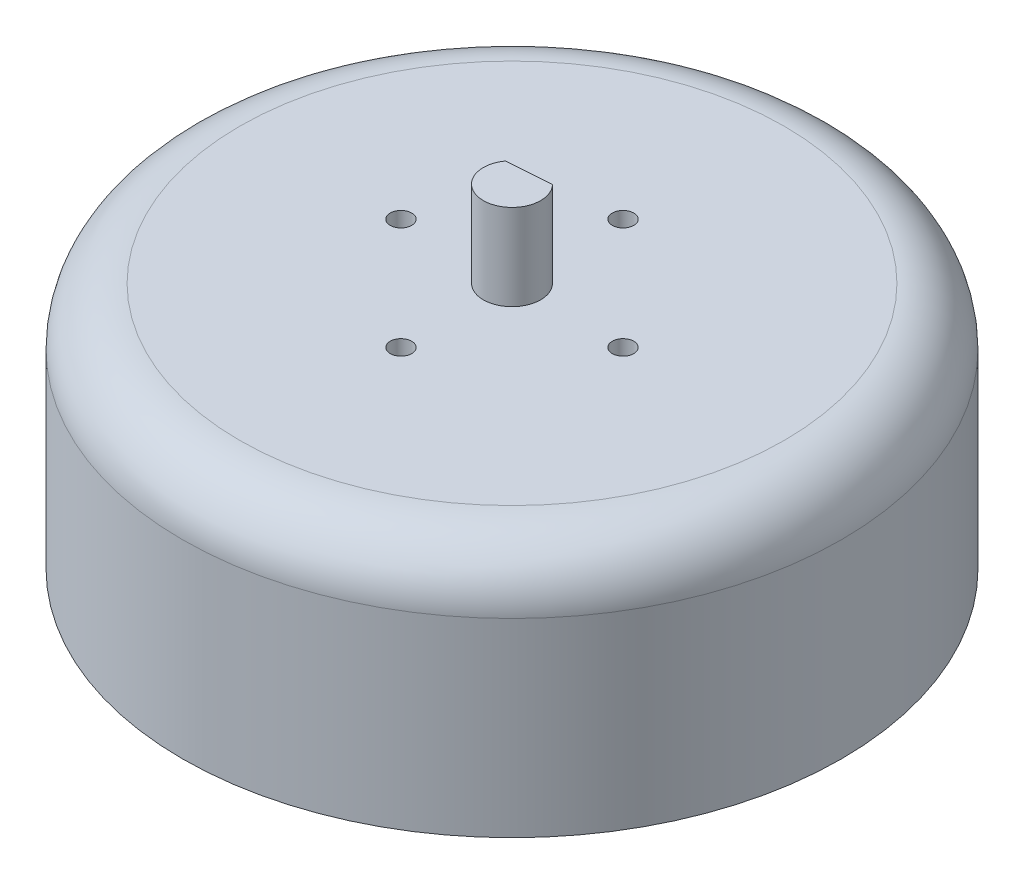
SolidWorks part; units mm, degrees
ref_plane "Front Plane" through (0, 0, 0) normal (0, 0, 1) x (1, 0, 0)
ref_plane "Top Plane" through (0, 0, 0) normal (0, 1, 0) x (1, 0, 0)
ref_plane "Right Plane" through (0, 0, 0) normal (1, 0, 0) x (0, 0, -1)
sketch "Sketch1" plane through (0, 0, 0) normal (0, 1, 0) x (1, 0, 0)
  circle A0 centre (0, 0) radius 46
  dimension "D1" = 92
extrude "Boss-Extrude1" add sketch "Sketch1" along normal blind 38.5
sketch "Sketch2" plane through (0, 0, 0) normal (0, 0, 1) x (1, 0, 0)
  line L0 (-46, 38.5) -> (-46, 30.5)
  line L1 (-46, 38.5) -> (-46, 0) construction
  line L2 (-46, 38.5) -> (-38, 38.5)
  line L3 (46, 38.5) -> (-46, 38.5) construction
  line L6 (0, 0) -> (0, 46.8045) construction
  arc A0 (-38, 38.5) -> (-46, 30.5) centre (-38, 30.5) ccw
  dimension "D1" = 8
  dimension "D2" = 8
revolve "Cut-Revolve1" cut sketch "Sketch2" angle 360 about L6
sketch "Sketch3" plane through (0, 0, 0) normal (0, 0, 1) x (1, 0, 0)
  line L0 (-46, 0) -> (-46, 4)
  line L1 (-46, 30.5) -> (-46, 0) construction
  line L2 (-46, 4) -> (-31, 0)
  line L3 (-46, 0) -> (46, 0) construction
  line L4 (-31, 0) -> (-46, 0)
  line L5 (0, 0) -> (0, 14.1784) construction
  dimension "D1" = 4
  dimension "D2" = 15
revolve "Cut-Revolve2" cut sketch "Sketch3" angle 360 about L5
sketch "Sketch4" plane through (0, 38.5, 0) normal (0, 1, 0) x (1, 0, 0)
  circle A0 centre (0, 0) radius 4
  dimension "D1" = 8
extrude "Boss-Extrude2" add sketch "Sketch4" along normal blind 12
sketch "Sketch5" plane through (0, 38.5, 0) normal (0, 1, 0) x (1, 0, 0)
  circle A0 centre (0, 0) radius 15.5 construction
  circle A1 centre (0, 0) radius 20 construction
  circle A2 centre (-15.5, 0) radius 1.5
  circle A3 centre (0, 15.5) radius 1.5
  circle A4 centre (15.5, 0) radius 1.5
  circle A5 centre (0, -15.5) radius 1.5
  point P15 (0, 0)
  dimension "D1" = 31
  dimension "D2" = 40
  dimension "D3" = 3
  dimension "D4" = 4
extrude "Cut-Extrude1" cut sketch "Sketch5" against normal blind 6
sketch "Sketch6" plane through (0, 50.5, 0) normal (0, 1, 0) x (1, 0, 0)
  line L0 (-3.2492, 2.333) -> (2.8945, 2.7608)
  circle A0 centre (0, 0) radius 4 construction
  arc A1 (2.8945, 2.7608) -> (-3.2492, 2.333) centre (0, 0) ccw
extrude "Cut-Extrude2" cut sketch "Sketch6" against normal blind 10
